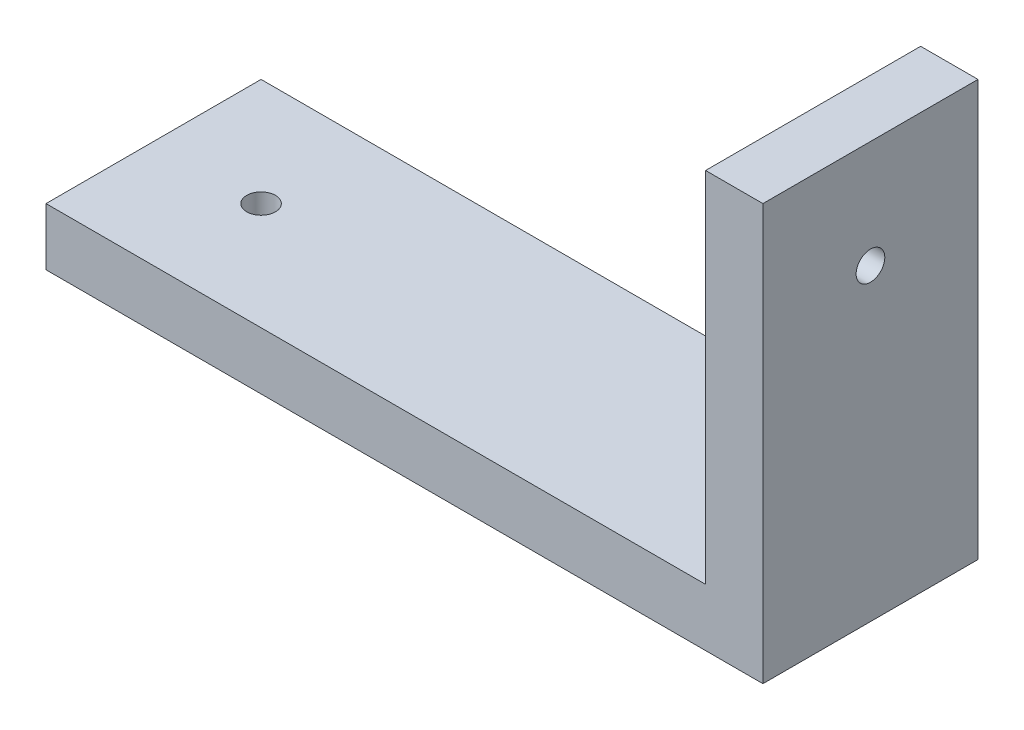
SolidWorks part; units mm, degrees
ref_plane "Front Plane" through (0, 0, 0) normal (0, 0, 1) x (1, 0, 0)
ref_plane "Top Plane" through (0, 0, 0) normal (0, 1, 0) x (1, 0, 0)
ref_plane "Right Plane" through (0, 0, 0) normal (1, 0, 0) x (0, 0, -1)
sketch "Sketch1" plane through (0, 0, 0) normal (0, 1, 0) x (1, 0, 0)
  line L1 (-50, 15) -> (50, 15)
  line L2 (-50, 15) -> (-50, -15)
  line L3 (-50, -15) -> (50, -15)
  line L4 (50, 15) -> (50, -15)
  line L5 (-50, 15) -> (50, -15) construction
  line L6 (-50, -15) -> (50, 15) construction
  circle A0 centre (-35, 0) radius 2
  point P0 (0, 0)
  dimension "D3" = 4
  dimension "D4" = 15
  dimension "D1" = 30
  dimension "D2" = 100
extrude "Boss-Extrude1" add sketch "Sketch1" along normal blind 8
sketch "Sketch2" plane through (0, 8, 0) normal (0, 1, 0) x (1, 0, 0)
  line L0 (-50, -15) -> (50, -15) construction
  line L1 (50, 15) -> (42, 15)
  line L2 (50, 15) -> (50, -15)
  line L3 (50, -15) -> (42, -15)
  line L4 (42, 15) -> (42, -15)
  dimension "D1" = 8
extrude "Boss-Extrude2" add sketch "Sketch2" along normal blind 50
sketch "Sketch3" plane through (50, 0, 0) normal (1, 0, 0) x (0, 0, -1)
  line L0 (-15, 58) -> (15, 58) construction
  line L1 (-15, 58) -> (-15, 0) construction
  circle A0 centre (0, 43) radius 2
  dimension "D1" = 4
  dimension "D2" = 15
  dimension "D3" = 15
extrude "Cut-Extrude1" cut sketch "Sketch3" against normal through all
